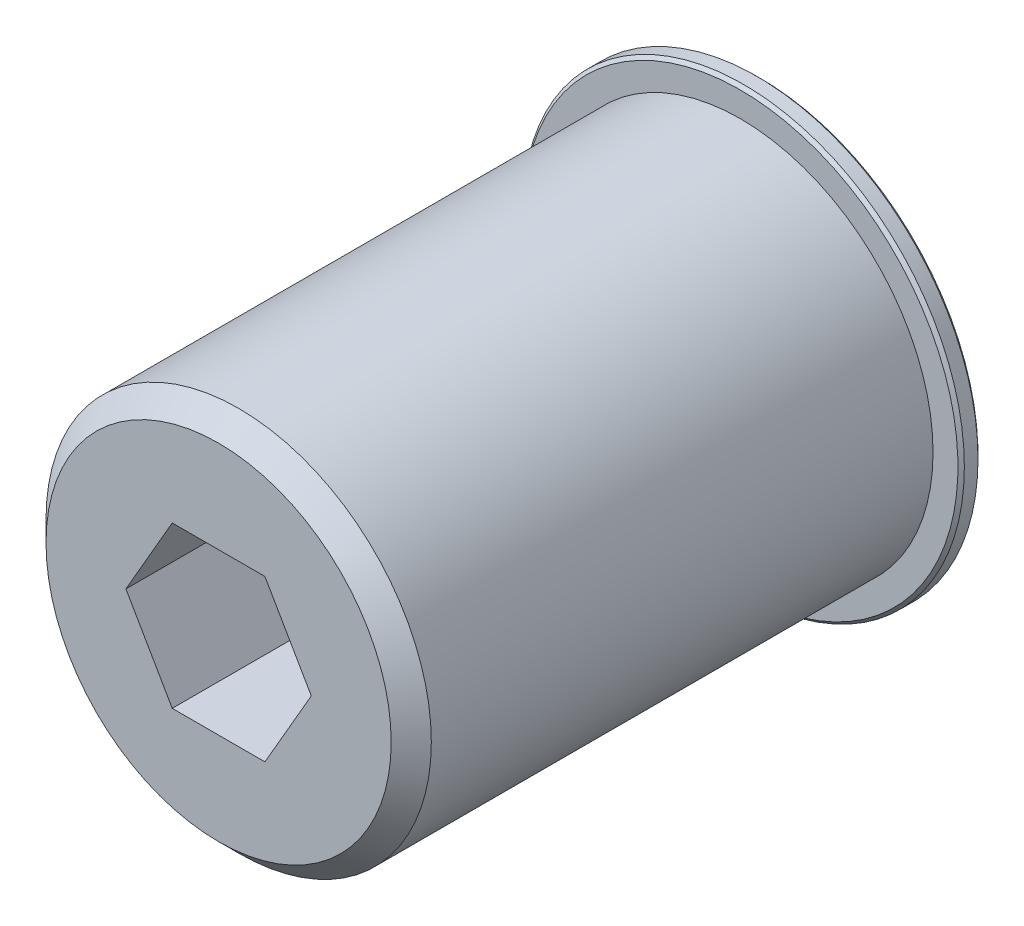
SolidWorks part; units mm, degrees
ref_plane "Front Plane" through (0, 0, 0) normal (0, 0, 1) x (1, 0, 0)
ref_plane "Top Plane" through (0, 0, 0) normal (0, 1, 0) x (1, 0, 0)
ref_plane "Right Plane" through (0, 0, 0) normal (1, 0, 0) x (0, 0, -1)
sketch "Sketch1" plane through (0, 0, 0) normal (0, 0, 1) x (1, 0, 0)
  circle A0 centre (0, 0) radius 15.24
  dimension "D1" = 30.48
extrude "Boss-Extrude1" add sketch "Sketch1" against normal mid plane 41.275
chamfer "Chamfer1" distance 1.5875 angle 45 1 edges at (15.24, 0, 20.6375)
sketch "Sketch2" plane through (0, 0, -20.6375) normal (0, 0, -1) x (-1, 0, 0)
  circle A0 centre (0, 0) radius 17.4625
  dimension "D1" = 34.925
extrude "Boss-Extrude2" add sketch "Sketch2" along normal blind 1.5875
sketch "Sketch3" plane through (0, 0, -22.225) normal (0, 0, -1) x (-1, 0, 0)
  line L1 (7.3323, 0) -> (3.6662, 6.35)
  line L2 (3.6662, 6.35) -> (-3.6662, 6.35)
  line L3 (-3.6662, 6.35) -> (-7.3323, 0)
  line L4 (-7.3323, 0) -> (-3.6662, -6.35)
  line L5 (-3.6662, -6.35) -> (3.6662, -6.35)
  line L6 (3.6662, -6.35) -> (7.3323, 0)
  circle A0 centre (0, 0) radius 6.35 construction
  dimension "D1" = 12.7
extrude "Cut-Extrude1" cut sketch "Sketch3" against normal through all
chamfer "Chamfer2" distance 0.254 angle 45 2 edges at (-17.4625, 0, -20.6375) (-17.4625, 0, -22.225)
